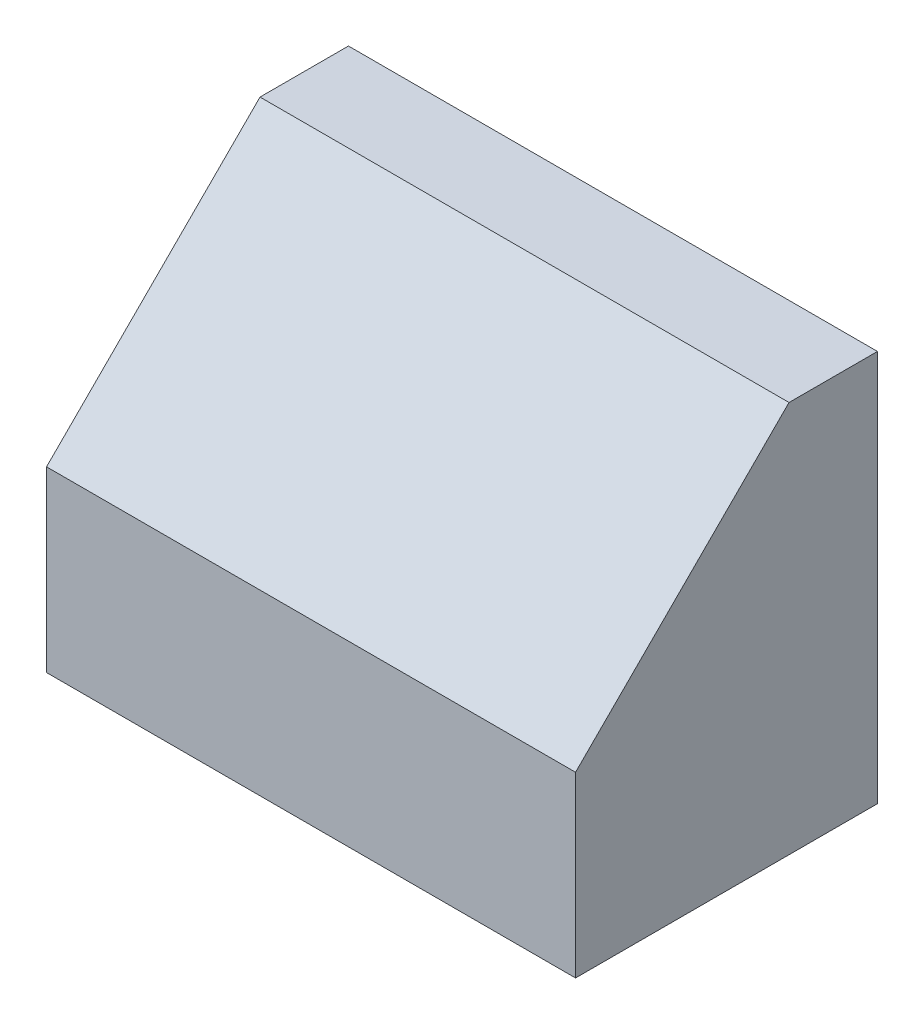
SolidWorks part; units mm, degrees
ref_plane "Ebene vorne" through (0, 0, 0) normal (0, 0, 1) x (1, 0, 0)
ref_plane "Ebene oben" through (0, 0, 0) normal (0, 1, 0) x (1, 0, 0)
ref_plane "Ebene rechts" through (0, 0, 0) normal (1, 0, 0) x (0, 0, -1)
sketch "Skizze1" plane through (0, 0, 0) normal (0, 0, 1) x (1, 0, 0)
  line L1 (77.8, -57.6) -> (-77.8, -57.6)
  line L2 (77.8, -57.6) -> (77.8, 57.6)
  line L3 (77.8, 57.6) -> (-77.8, 57.6)
  line L4 (-77.8, -57.6) -> (-77.8, 57.6)
  line L5 (77.8, -57.6) -> (-77.8, 57.6) construction
  line L6 (77.8, 57.6) -> (-77.8, -57.6) construction
  point P0 (0, 0)
  dimension "D1" = 115.2
  dimension "D2" = 155.6
extrude "Aufsatz-Linear austragen1" add sketch "Skizze1" along normal blind 88.8
sketch "Skizze6" plane through (-77.8, 0, 0) normal (-1, 0, 0) x (0, 0, 1)
  line L0 (26.0089, 57.6) -> (88.8, -5.1911)
  line L1 (88.8, 57.6) -> (0, 57.6) construction
  line L2 (88.8, 57.6) -> (88.8, -57.6) construction
  line L3 (88.8, -5.1911) -> (88.8, 57.6)
  line L4 (88.8, 57.6) -> (26.0089, 57.6)
  dimension "D1" = 88.8
  dimension "D2" = 45
extrude "Schnitt-Linear austragen1" cut sketch "Skizze6" against normal through all
